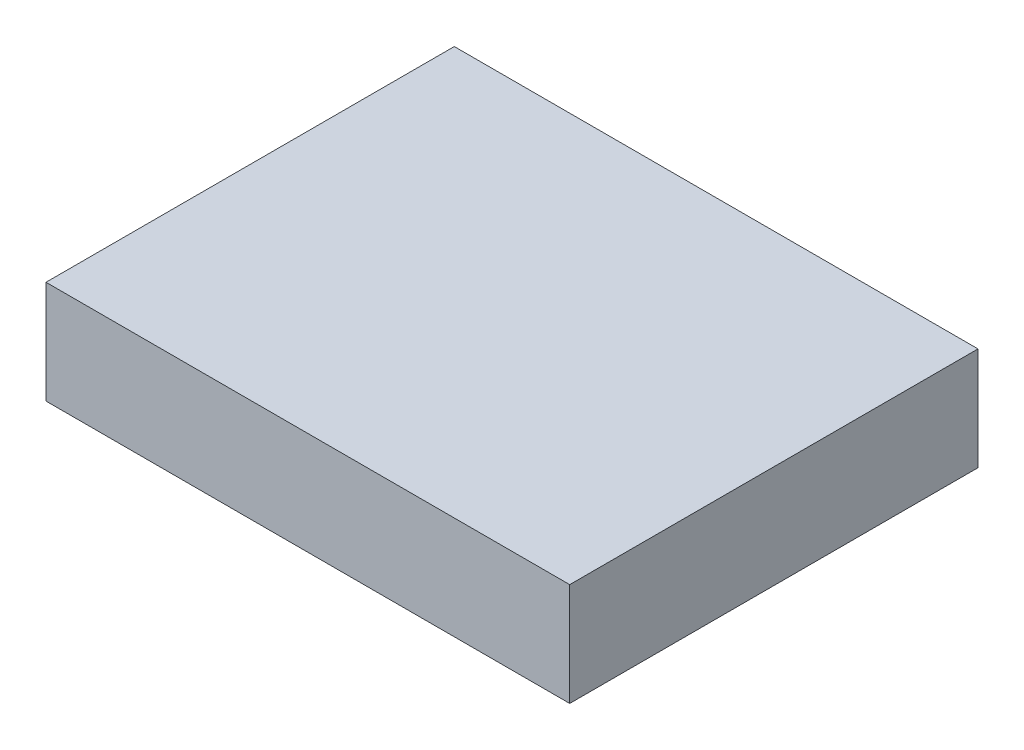
SolidWorks part; units mm, degrees
ref_plane "Front Plane" through (0, 0, 0) normal (0, 0, 1) x (1, 0, 0)
ref_plane "Top Plane" through (0, 0, 0) normal (0, 1, 0) x (1, 0, 0)
ref_plane "Right Plane" through (0, 0, 0) normal (1, 0, 0) x (0, 0, -1)
sketch "Sketch1" plane through (0, 0, 0) normal (0, 1, 0) x (1, 0, 0)
  line L1 (-25.4423, -19.8349) -> (25.4423, -19.8349)
  line L2 (-25.4423, -19.8349) -> (-25.4423, 19.8349)
  line L3 (-25.4423, 19.8349) -> (25.4423, 19.8349)
  line L4 (25.4423, -19.8349) -> (25.4423, 19.8349)
  line L5 (-25.4423, -19.8349) -> (25.4423, 19.8349) construction
  line L6 (-25.4423, 19.8349) -> (25.4423, -19.8349) construction
  point P0 (0, 0)
extrude "Boss-Extrude1" add sketch "Sketch1" along normal blind 10
